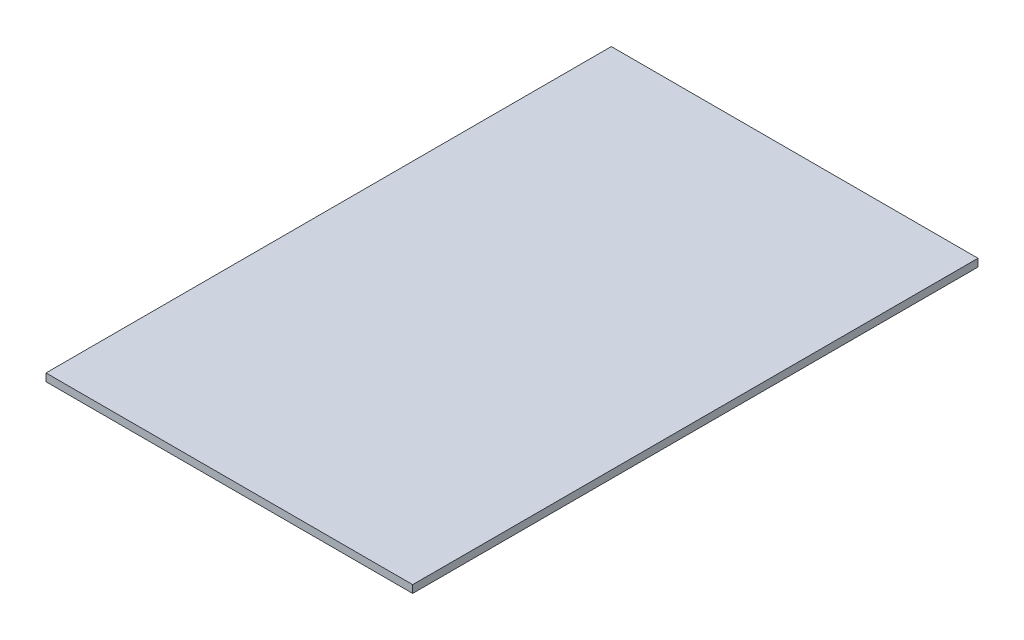
SolidWorks part; units mm, degrees
ref_plane "Front Plane" through (0, 0, 0) normal (0, 0, 1) x (1, 0, 0)
ref_plane "Top Plane" through (0, 0, 0) normal (0, 1, 0) x (1, 0, 0)
ref_plane "Right Plane" through (0, 0, 0) normal (1, 0, 0) x (0, 0, -1)
sketch "Sketch1" plane through (0, 0, 0) normal (0, 1, 0) x (1, 0, 0)
  line L1 (0, 0) -> (304.8, 0)
  line L2 (0, 0) -> (0, 469.9)
  line L3 (0, 469.9) -> (304.8, 469.9)
  line L4 (304.8, 0) -> (304.8, 469.9)
  dimension "D1" = 304.8
  dimension "D2" = 469.9
extrude "Boss-Extrude1" add sketch "Sketch1" along normal blind 6.35
ref_plane "Plane1" through (0, 0, -234.95) normal (0, 0, -1) x (-1, 0, 0)
ref_plane "Plane2" through (152.4, 0, 0) normal (1, 0, 0) x (0, 0, -1)
